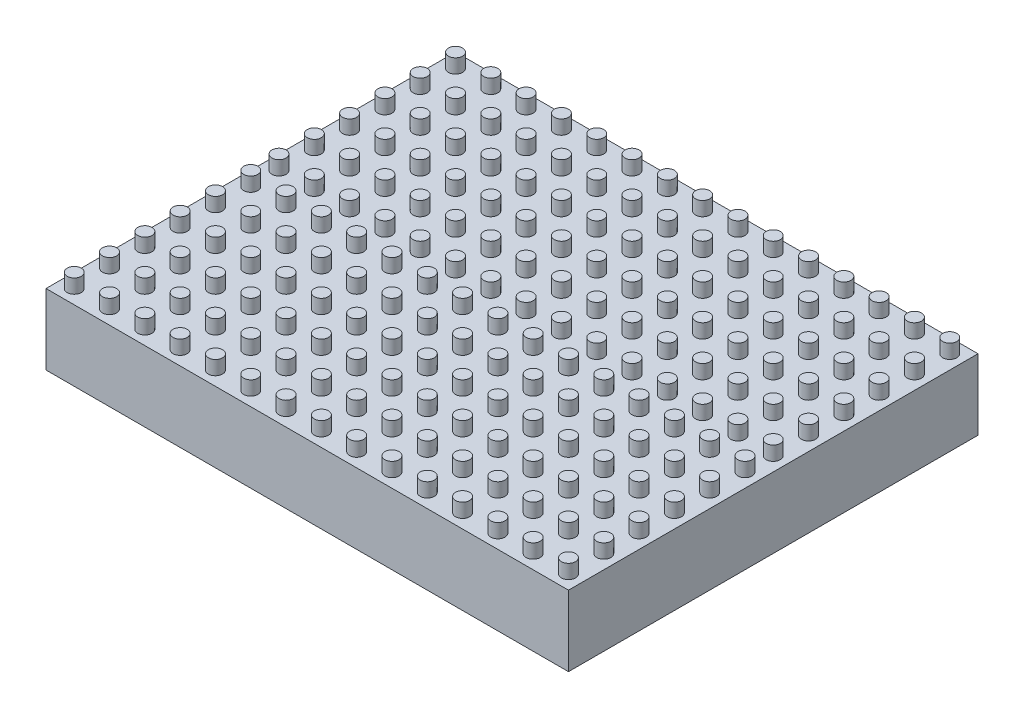
SolidWorks part; units mm, degrees
ref_plane "前视基准面" through (0, 0, 0) normal (0, 0, 1) x (1, 0, 0)
ref_plane "上视基准面" through (0, 0, 0) normal (0, 1, 0) x (1, 0, 0)
ref_plane "右视基准面" through (0, 0, 0) normal (1, 0, 0) x (0, 0, -1)
other "Configuration Table"
sketch "草图1" plane through (0, 0, 0) normal (0, 1, 0) x (1, 0, 0)
  line L1 (-370, 290) -> (370, 290)
  line L2 (-370, 290) -> (-370, -290)
  line L3 (-370, -290) -> (370, -290)
  line L4 (370, 290) -> (370, -290)
  line L5 (-370, 290) -> (370, -290) construction
  line L6 (-370, -290) -> (370, 290) construction
  point P0 (0, 0)
  dimension "D1" = 740
  dimension "D2" = 580
extrude "凸台-拉伸1" add sketch "草图1" along normal blind 100
ref_plane "基准面1" through (0, 100, 0) normal (0, 1, 0) x (1, 0, 0)
sketch "草图2" plane through (0, 100, 0) normal (0, 1, 0) x (1, 0, 0)
  line L4 (370, -290) -> (370, 290)
  line L5 (370, 290) -> (-370, 290)
  line L6 (-370, 290) -> (-370, -290)
  line L7 (-370, -290) -> (370, -290)
  line L8 (370, -290) -> (370, 290) construction
  line L9 (370, 290) -> (-370, 290) construction
  line L10 (-370, 290) -> (-370, -290) construction
  line L11 (-370, -290) -> (370, -290) construction
  circle A0 centre (-350, 270) radius 10
  circle A1 centre (-300, 270) radius 10
  circle A2 centre (-250, 270) radius 10
  circle A3 centre (-200, 270) radius 10
  circle A4 centre (-150, 270) radius 10
  circle A5 centre (-100, 270) radius 10
  circle A6 centre (-50, 270) radius 10
  circle A7 centre (0, 270) radius 10
  circle A8 centre (50, 270) radius 10
  circle A9 centre (100, 270) radius 10
  circle A10 centre (150, 270) radius 10
  circle A11 centre (200, 270) radius 10
  circle A12 centre (250, 270) radius 10
  circle A13 centre (300, 270) radius 10
  circle A14 centre (350, 270) radius 10
  circle A15 centre (-300, 220) radius 10
  circle A16 centre (-250, 220) radius 10
  circle A17 centre (-200, 220) radius 10
  circle A18 centre (-150, 220) radius 10
  circle A19 centre (-100, 220) radius 10
  circle A20 centre (-50, 220) radius 10
  circle A21 centre (0, 220) radius 10
  circle A22 centre (50, 220) radius 10
  circle A23 centre (100, 220) radius 10
  circle A24 centre (150, 220) radius 10
  circle A25 centre (200, 220) radius 10
  circle A26 centre (250, 220) radius 10
  circle A27 centre (300, 220) radius 10
  circle A28 centre (350, 220) radius 10
  circle A29 centre (-300, 170) radius 10
  circle A30 centre (-250, 170) radius 10
  circle A31 centre (-200, 170) radius 10
  circle A32 centre (-150, 170) radius 10
  circle A33 centre (-100, 170) radius 10
  circle A34 centre (-50, 170) radius 10
  circle A35 centre (0, 170) radius 10
  circle A36 centre (50, 170) radius 10
  circle A37 centre (100, 170) radius 10
  circle A38 centre (150, 170) radius 10
  circle A39 centre (200, 170) radius 10
  circle A40 centre (250, 170) radius 10
  circle A41 centre (300, 170) radius 10
  circle A42 centre (350, 170) radius 10
  circle A43 centre (-300, 120) radius 10
  circle A44 centre (-250, 120) radius 10
  circle A45 centre (-200, 120) radius 10
  circle A46 centre (-150, 120) radius 10
  circle A47 centre (-100, 120) radius 10
  circle A48 centre (-50, 120) radius 10
  circle A49 centre (0, 120) radius 10
  circle A50 centre (50, 120) radius 10
  circle A51 centre (100, 120) radius 10
  circle A52 centre (150, 120) radius 10
  circle A53 centre (200, 120) radius 10
  circle A54 centre (250, 120) radius 10
  circle A55 centre (300, 120) radius 10
  circle A56 centre (350, 120) radius 10
  circle A57 centre (-300, 70) radius 10
  circle A58 centre (-250, 70) radius 10
  circle A59 centre (-200, 70) radius 10
  circle A60 centre (-150, 70) radius 10
  circle A61 centre (-100, 70) radius 10
  circle A62 centre (-50, 70) radius 10
  circle A63 centre (0, 70) radius 10
  circle A64 centre (50, 70) radius 10
  circle A65 centre (100, 70) radius 10
  circle A66 centre (150, 70) radius 10
  circle A67 centre (200, 70) radius 10
  circle A68 centre (250, 70) radius 10
  circle A69 centre (300, 70) radius 10
  circle A70 centre (350, 70) radius 10
  circle A71 centre (-300, 20) radius 10
  circle A72 centre (-250, 20) radius 10
  circle A73 centre (-200, 20) radius 10
  circle A74 centre (-150, 20) radius 10
  circle A75 centre (-100, 20) radius 10
  circle A76 centre (-50, 20) radius 10
  circle A77 centre (0, 20) radius 10
  circle A78 centre (50, 20) radius 10
  circle A79 centre (100, 20) radius 10
  circle A80 centre (150, 20) radius 10
  circle A81 centre (200, 20) radius 10
  circle A82 centre (250, 20) radius 10
  circle A83 centre (300, 20) radius 10
  circle A84 centre (350, 20) radius 10
  circle A85 centre (-350, 220) radius 10
  circle A86 centre (-350, 170) radius 10
  circle A87 centre (-350, 120) radius 10
  circle A88 centre (-350, 70) radius 10
  circle A89 centre (-350, 20) radius 10
  circle A90 centre (350, -270) radius 10
  circle A91 centre (300, -270) radius 10
  circle A92 centre (250, -270) radius 10
  circle A93 centre (200, -270) radius 10
  circle A94 centre (150, -270) radius 10
  circle A95 centre (100, -270) radius 10
  circle A96 centre (50, -270) radius 10
  circle A97 centre (0, -270) radius 10
  circle A98 centre (-50, -270) radius 10
  circle A99 centre (-100, -270) radius 10
  circle A100 centre (-150, -270) radius 10
  circle A101 centre (-200, -270) radius 10
  circle A102 centre (-250, -270) radius 10
  circle A103 centre (-300, -270) radius 10
  circle A104 centre (-350, -270) radius 10
  circle A105 centre (300, -220) radius 10
  circle A106 centre (250, -220) radius 10
  circle A107 centre (200, -220) radius 10
  circle A108 centre (150, -220) radius 10
  circle A109 centre (100, -220) radius 10
  circle A110 centre (50, -220) radius 10
  circle A111 centre (0, -220) radius 10
  circle A112 centre (-50, -220) radius 10
  circle A113 centre (-100, -220) radius 10
  circle A114 centre (-150, -220) radius 10
  circle A115 centre (-200, -220) radius 10
  circle A116 centre (-250, -220) radius 10
  circle A117 centre (-300, -220) radius 10
  circle A118 centre (-350, -220) radius 10
  circle A119 centre (300, -170) radius 10
  circle A120 centre (250, -170) radius 10
  circle A121 centre (200, -170) radius 10
  circle A122 centre (150, -170) radius 10
  circle A123 centre (100, -170) radius 10
  circle A124 centre (50, -170) radius 10
  circle A125 centre (0, -170) radius 10
  circle A126 centre (-50, -170) radius 10
  circle A127 centre (-100, -170) radius 10
  circle A128 centre (-150, -170) radius 10
  circle A129 centre (-200, -170) radius 10
  circle A130 centre (-250, -170) radius 10
  circle A131 centre (-300, -170) radius 10
  circle A132 centre (-350, -170) radius 10
  circle A133 centre (300, -120) radius 10
  circle A134 centre (250, -120) radius 10
  circle A135 centre (200, -120) radius 10
  circle A136 centre (150, -120) radius 10
  circle A137 centre (100, -120) radius 10
  circle A138 centre (50, -120) radius 10
  circle A139 centre (0, -120) radius 10
  circle A140 centre (-50, -120) radius 10
  circle A141 centre (-100, -120) radius 10
  circle A142 centre (-150, -120) radius 10
  circle A143 centre (-200, -120) radius 10
  circle A144 centre (-250, -120) radius 10
  circle A145 centre (-300, -120) radius 10
  circle A146 centre (-350, -120) radius 10
  circle A147 centre (300, -70) radius 10
  circle A148 centre (250, -70) radius 10
  circle A149 centre (200, -70) radius 10
  circle A150 centre (150, -70) radius 10
  circle A151 centre (100, -70) radius 10
  circle A152 centre (50, -70) radius 10
  circle A153 centre (0, -70) radius 10
  circle A154 centre (-50, -70) radius 10
  circle A155 centre (-100, -70) radius 10
  circle A156 centre (-150, -70) radius 10
  circle A157 centre (-200, -70) radius 10
  circle A158 centre (-250, -70) radius 10
  circle A159 centre (-300, -70) radius 10
  circle A160 centre (-350, -70) radius 10
  circle A161 centre (300, -20) radius 10
  circle A162 centre (250, -20) radius 10
  circle A163 centre (200, -20) radius 10
  circle A164 centre (150, -20) radius 10
  circle A165 centre (100, -20) radius 10
  circle A166 centre (50, -20) radius 10
  circle A167 centre (0, -20) radius 10
  circle A168 centre (-50, -20) radius 10
  circle A169 centre (-100, -20) radius 10
  circle A170 centre (-150, -20) radius 10
  circle A171 centre (-200, -20) radius 10
  circle A172 centre (-250, -20) radius 10
  circle A173 centre (-300, -20) radius 10
  circle A174 centre (-350, -20) radius 10
  circle A175 centre (350, -220) radius 10
  circle A176 centre (350, -170) radius 10
  circle A177 centre (350, -120) radius 10
  circle A178 centre (350, -70) radius 10
  circle A179 centre (350, -20) radius 10
  dimension "D2" = 20
  dimension "D9" = 20
  dimension "D3" = 20
  dimension "D4" = 20
  dimension "D7" = 20
  dimension "D8" = 20
  dimension "D1" = 0
  dimension "D5" = 15
  dimension "D6" = 6
  dimension "D10" = 15
  dimension "D11" = 6
extrude "凸台-拉伸3" add sketch "草图2" along normal blind 20
ref_plane "基准面2" through (0, -200, 0) normal (0, -1, 0) x (-1, 0, 0)
sketch "草图3" plane through (0, -200, 0) normal (0, -1, 0) x (-1, 0, 0)
  line L1 (-90, 50) -> (90, 50)
  line L2 (-90, 50) -> (-90, -50)
  line L3 (-90, -50) -> (90, -50)
  line L4 (90, 50) -> (90, -50)
  line L5 (-90, 50) -> (90, -50) construction
  line L6 (-90, -50) -> (90, 50) construction
  point P0 (0, 0)
  dimension "D1" = 180
  dimension "D2" = 100
loft "放样1" add profiles "草图3" section "草图3" section face at (0, 0, 0)
